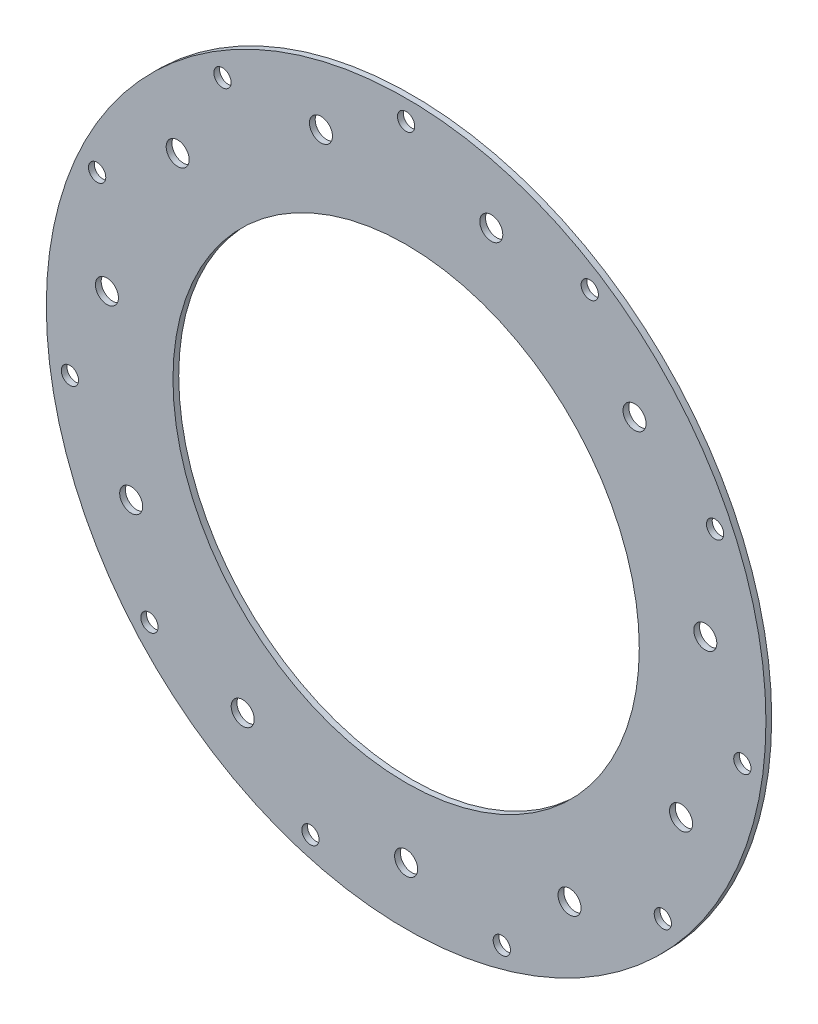
SolidWorks part; units mm, degrees
ref_plane "前视基准面" through (0, 0, 0) normal (0, 0, 1) x (1, 0, 0)
ref_plane "上视基准面" through (0, 0, 0) normal (0, 1, 0) x (1, 0, 0)
ref_plane "右视基准面" through (0, 0, 0) normal (1, 0, 0) x (0, 0, -1)
sketch "草图1" plane through (0, 0, 0) normal (0, 0, 1) x (1, 0, 0)
  line L0 (-28.3836, -44.1658) -> (0, -52.5) construction
  line L1 (-14.1918, -48.3329) -> (-20.9087, -71.2083) construction
  circle A0 centre (0, 0) radius 40.5
  circle A1 centre (0, 0) radius 62.5
  circle A2 centre (0, 0) radius 59 construction
  circle A19 centre (0, 0) radius 52.5 construction
  circle A20 centre (0, -52.5) radius 2
  circle A21 centre (-28.3836, -44.1658) radius 2
  circle A22 centre (-47.7557, -21.8093) radius 2
  circle A23 centre (-51.9656, 7.4715) radius 2
  circle A24 centre (-39.6769, 34.3802) radius 2
  circle A25 centre (-14.791, 50.3734) radius 2
  circle A26 centre (14.791, 50.3734) radius 2
  circle A27 centre (39.6769, 34.3802) radius 2
  circle A28 centre (51.9656, 7.4715) radius 2
  circle A29 centre (47.7557, -21.8093) radius 2
  circle A30 centre (28.3836, -44.1658) radius 2
  circle A31 centre (-16.6222, -56.6101) radius 1.5
  circle A32 centre (-44.5892, -38.6368) radius 1.5
  circle A33 centre (-58.3995, -8.3966) radius 1.5
  circle A34 centre (-53.6683, 24.5095) radius 1.5
  circle A35 centre (-31.8978, 49.634) radius 1.5
  circle A36 centre (0, 59) radius 1.5
  circle A37 centre (31.8978, 49.634) radius 1.5
  circle A38 centre (53.6683, 24.5095) radius 1.5
  circle A39 centre (58.3995, -8.3966) radius 1.5
  circle A40 centre (44.5892, -38.6368) radius 1.5
  circle A41 centre (16.6222, -56.6101) radius 1.5
  dimension "D1" = 81
  dimension "D2" = 125
  dimension "D3" = 118
  dimension "D4" = 3
  dimension "D6" = 105
  dimension "D7" = 4
  dimension "D8" = 11
  dimension "D5" = 11
extrude "凸台-拉伸1" add sketch "草图1" along normal blind 1
equation "\"52.5×2\"=96.9638"
